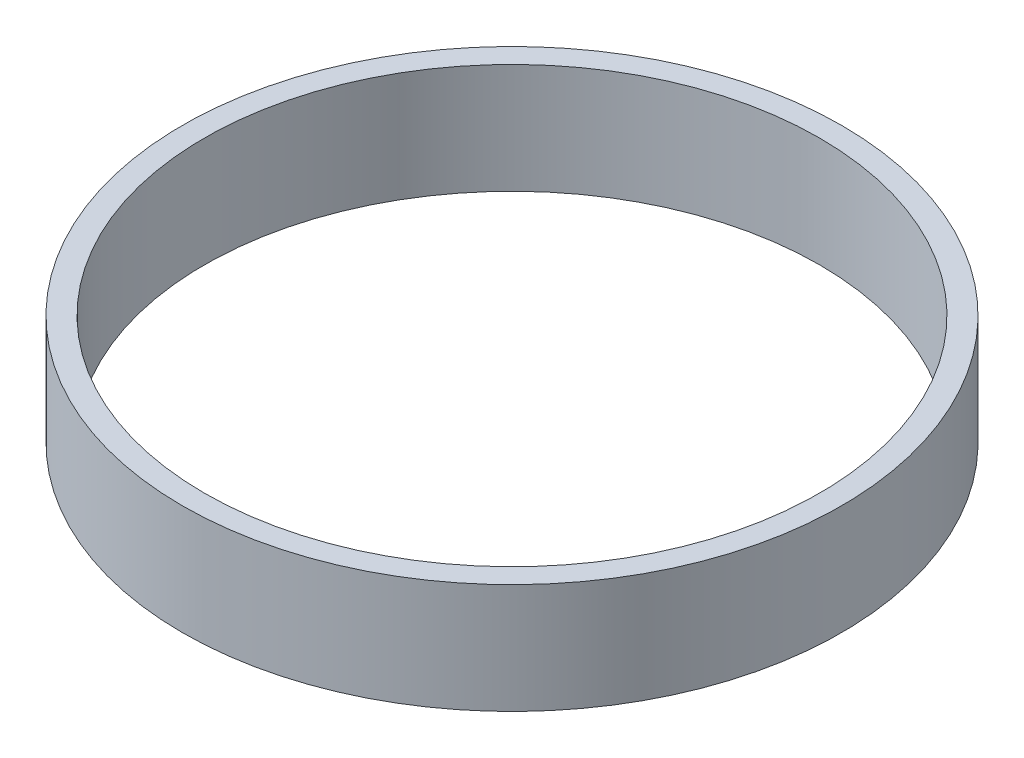
SolidWorks part; units mm, degrees
ref_plane "Front Plane" through (0, 0, 0) normal (0, 0, 1) x (1, 0, 0)
ref_plane "Top Plane" through (0, 0, 0) normal (0, 1, 0) x (1, 0, 0)
ref_plane "Right Plane" through (0, 0, 0) normal (1, 0, 0) x (0, 0, -1)
sketch "Sketch1" plane through (0, 0, 0) normal (0, 1, 0) x (1, 0, 0)
  circle A0 centre (0, 0) radius 28
  circle A1 centre (0, 0) radius 30
  dimension "D1" = 60
  dimension "D2" = 2
extrude "Boss-Extrude1" add sketch "Sketch1" along normal blind 10
